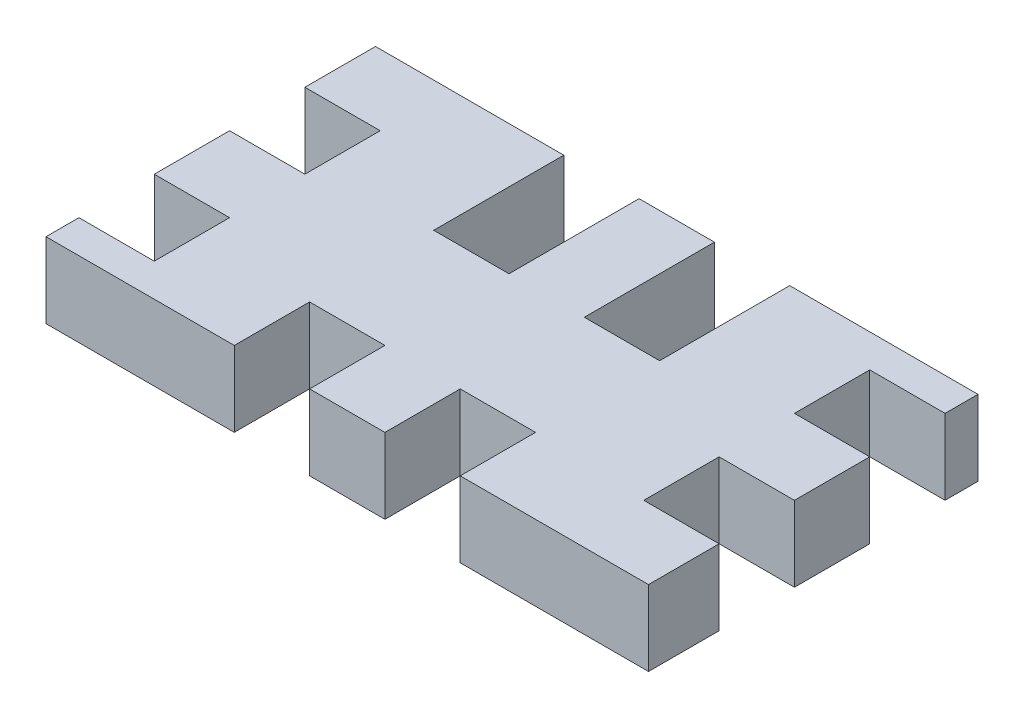
SolidWorks part; units mm, degrees
ref_plane "前视" through (0, 0, 0) normal (0, 0, 1) x (1, 0, 0)
ref_plane "上视" through (0, 0, 0) normal (0, 1, 0) x (1, 0, 0)
ref_plane "右视" through (0, 0, 0) normal (1, 0, 0) x (0, 0, -1)
sketch "草图1" plane through (0, 0, 0) normal (0, 1, 0) x (1, 0, 0)
  line L0 (-43.9252, 7.7488) -> (-43.9252, -8.2512)
  line L1 (-43.9252, 38.7488) -> (-3.9252, 38.7488)
  line L2 (-43.9252, 38.7488) -> (-43.9252, 23.7488)
  line L3 (-43.9252, -31.2512) -> (-3.9252, -31.2512)
  line L4 (84.0748, 38.7488) -> (84.0748, 31.7488)
  line L5 (-43.9252, 23.7488) -> (-27.9252, 23.7488)
  line L6 (-43.9252, -24.2512) -> (-43.9252, -31.2512)
  line L7 (-43.9252, 7.7488) -> (-27.9252, 7.7488)
  line L8 (-27.9252, 23.7488) -> (-27.9252, 7.7488)
  line L9 (-43.9252, -8.2512) -> (-27.9252, -8.2512)
  line L10 (12.0748, -31.2512) -> (28.0748, -31.2512)
  line L11 (-43.9252, -24.2512) -> (-27.9252, -24.2512)
  line L12 (-27.9252, -8.2512) -> (-27.9252, -24.2512)
  line L14 (-3.9252, 38.7488) -> (-3.9252, 11.1115)
  line L15 (-3.9252, 11.1115) -> (12.0748, 11.1115)
  line L16 (12.0748, 38.7488) -> (12.0748, 11.1115)
  line L17 (12.0748, 38.7488) -> (28.0748, 38.7488)
  line L18 (28.0748, 38.7488) -> (28.0748, 11.1115)
  line L19 (28.0748, 11.1115) -> (44.0748, 11.1115)
  line L20 (44.0748, 38.7488) -> (44.0748, 11.1115)
  line L21 (44.0748, -31.2512) -> (84.0748, -31.2512)
  line L22 (-3.9252, -31.2512) -> (-3.9252, -15.2512)
  line L23 (-3.9252, -15.2512) -> (12.0748, -15.2512)
  line L24 (12.0748, -31.2512) -> (12.0748, -15.2512)
  line L25 (84.0748, -16.2512) -> (84.0748, -31.2512)
  line L26 (28.0748, -31.2512) -> (28.0748, -15.2512)
  line L27 (28.0748, -15.2512) -> (44.0748, -15.2512)
  line L28 (44.0748, -31.2512) -> (44.0748, -15.2512)
  line L29 (84.0748, 31.7488) -> (68.0748, 31.7488)
  line L30 (44.0748, 38.7488) -> (84.0748, 38.7488)
  line L31 (84.0748, 15.7488) -> (68.0748, 15.7488)
  line L32 (68.0748, 31.7488) -> (68.0748, 15.7488)
  line L33 (84.0748, -0.2512) -> (68.0748, -0.2512)
  line L34 (84.0748, 15.7488) -> (84.0748, -0.2512)
  line L35 (84.0748, -16.2512) -> (68.0748, -16.2512)
  line L36 (68.0748, -0.2512) -> (68.0748, -16.2512)
  dimension "D1" = 70
  dimension "D2" = 128
  dimension "D3" = 16
  dimension "D4" = 16
  dimension "D5" = 16
  dimension "D7" = 16
  dimension "D8" = 16
  dimension "D9" = 16
  dimension "D10" = 40
  dimension "D11" = 40
  dimension "D12" = 16
  dimension "D13" = 16
  dimension "D14" = 7
  dimension "D15" = 16
  dimension "D16" = 16
  dimension "D17" = 16
  dimension "D18" = 40
  dimension "D19" = 16
  dimension "D20" = 16
  dimension "D21" = 16
  dimension "D22" = 16
  dimension "D23" = 16
  dimension "D24" = 16
  dimension "D25" = 26.3627
extrude "凸台-拉伸1" add sketch "草图1" along normal blind 16
